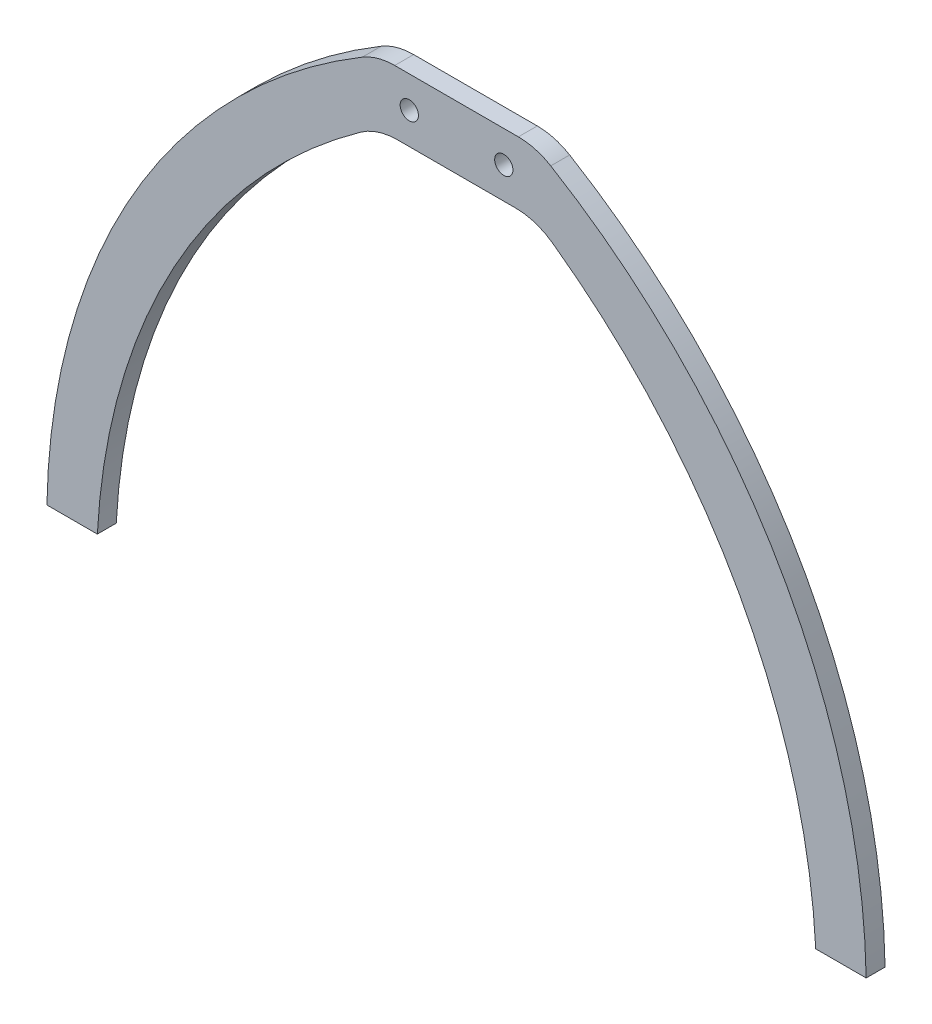
SolidWorks part; units mm, degrees
material "Thornel Mat VMA"
ref_plane "前视基准面" through (0, 0, 0) normal (0, 0, 1) x (1, 0, 0)
ref_plane "上视基准面" through (0, 0, 0) normal (0, 1, 0) x (1, 0, 0)
ref_plane "右视基准面" through (0, 0, 0) normal (1, 0, 0) x (0, 0, -1)
other "Configuration Table"
sketch "草图1" plane through (0, 0, 0) normal (0, 0, 1) x (1, 0, 0)
  line L0 (-29.2138, -78) -> (59.1254, -78) construction
  line L1 (0, 5) -> (25, 5) construction
  line L2 (0, 0) -> (25, 0)
  line L3 (0, 0) -> (0, 10) construction
  line L4 (0, 10) -> (25, 10)
  line L5 (25, 0) -> (25, 10) construction
  line L6 (5, 5) -> (20, 5) construction
  line L7 (12.5, 5) -> (12.5, -84.4122) construction
  line L8 (-52.5, -78) -> (-44.5, -78)
  line L9 (-44.5, -78) -> (69.5, -78) construction
  line L10 (69.5, -78) -> (77.5, -78)
  line L11 (12.5, -78) -> (12.5, 0) construction
  circle A0 centre (5, 5) radius 1.45
  circle A1 centre (20, 5) radius 1.45
  arc A2 (0, 10) -> (-52.5, -78) centre (50.4846, -79.7792) ccw
  arc A3 (0, 0) -> (-44.5, -78) centre (55.3606, -83.2779) ccw
  arc A4 (25, 0) -> (69.5, -78) centre (-30.3606, -83.2779) cw
  arc A5 (25, 10) -> (77.5, -78) centre (-25.4846, -79.7792) cw
  dimension "D3" = 2.9
  dimension "D5" = 83
  dimension "D9" = 103
  dimension "D10" = 100
  dimension "D1" = 25
  dimension "D2" = 10
  dimension "D4" = 15
  dimension "D6" = 8
  dimension "D7" = 8
  dimension "D8" = 130
extrude "凸台-拉伸1" add sketch "草图1" along normal blind 3
fillet "圆角1" radius 10 4 edges at (25, 10, 1.5) (0, 10, 1.5) (25, 0, 1.5) (0, 0, 1.5)
